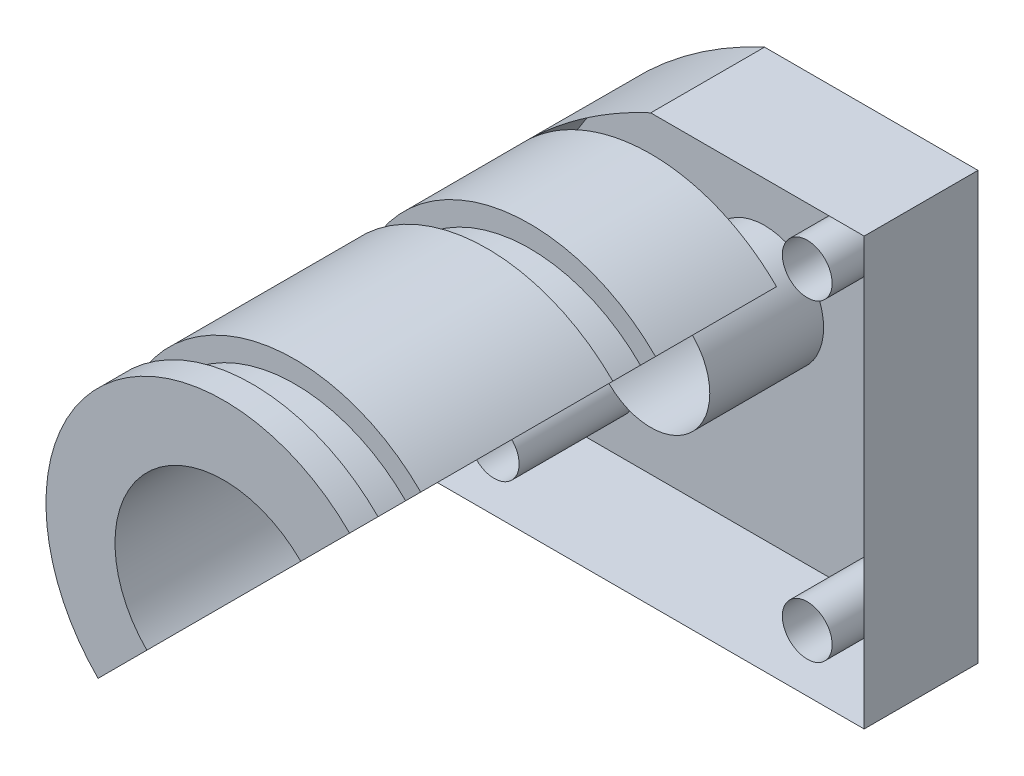
SolidWorks part; units mm, degrees
ref_plane "Ön Düzlem" through (0, 0, 0) normal (0, 0, 1) x (1, 0, 0)
ref_plane "Üst Düzlem" through (0, 0, 0) normal (0, 1, 0) x (1, 0, 0)
ref_plane "Sağ Düzlem" through (0, 0, 0) normal (1, 0, 0) x (0, 0, -1)
sketch "Çizim1" plane through (0, 0, 0) normal (0, 0, 1) x (1, 0, 0)
  line L1 (0, 0) -> (30, 0)
  line L2 (0, 0) -> (0, 30)
  line L3 (0, 30) -> (30, 30)
  line L4 (30, 0) -> (30, 30)
  dimension "D1" = 30
extrude "Yükseklik-Ekstrüzyon1" add sketch "Çizim1" along normal blind 8
sketch "Çizim2" plane through (0, 0, 8) normal (0, 0, 1) x (1, 0, 0)
  line L0 (6.1612, 6.1612) -> (9.5906, 9.5906)
  line L1 (20.4094, 20.4094) -> (23.8388, 23.8388)
  line L3 (30, 30) -> (0, 0) construction
  arc A0 (6.1612, 6.1612) -> (23.8388, 23.8388) centre (15, 15) cw
  arc A1 (9.5906, 9.5906) -> (20.4094, 20.4094) centre (15, 15) cw
  dimension "D1" = 12.5
  dimension "D2" = 7.65
sketch "Çizim3" plane through (0, 0, 8) normal (0, 0, 1) x (1, 0, 0)
  line L0 (30, 30) -> (0, 30) construction
  line L1 (0, 30) -> (0, 0) construction
  line L2 (30, 0) -> (30, 30) construction
  line L3 (0, 0) -> (30, 0) construction
  circle A0 centre (4, 26) radius 1.75
  circle A1 centre (4, 4) radius 1.75
  circle A2 centre (26, 26) radius 1.75
  circle A3 centre (26, 4) radius 1.75
  point P8 (0, 0)
  point P9 (0, 0)
  point P10 (0, 0)
  point P11 (0, 0)
  dimension "D1" = 3.5
  dimension "D2" = 4
  dimension "D3" = 4
  dimension "D4" = 4
  dimension "D5" = 4
extrude "Kes-Ekstrüzyon1" cut sketch "Çizim3" against normal blind 30
extrude "Yükseklik-Ekstrüzyon3" add sketch "Çizim2" along normal blind 30
sketch "Çizim4" plane through (0, 0, 8) normal (0, 0, 1) x (1, 0, 0)
  line L0 (0, 30) -> (0, 0) construction
  line L1 (30, 30) -> (0, 30) construction
  line L2 (0, 15) -> (0, 30)
  line L3 (0, 30) -> (15, 30)
  arc A0 (0, 15) -> (15, 30) centre (27.8377, 2.1623) cw
  arc A1 (23.8388, 23.8388) -> (6.1612, 6.1612) centre (15, 15) ccw construction
extrude "Kes-Ekstrüzyon2" cut sketch "Çizim4" against normal blind 30
sketch "Çizim5" plane through (0, 0, 8) normal (0, 0, 1) x (1, 0, 0)
  circle A0 centre (15, 15) radius 4.15
  arc A1 (20.4094, 20.4094) -> (9.5906, 9.5906) centre (15, 15) ccw construction
  dimension "D1" = 8.3
extrude "Kes-Ekstrüzyon3" cut sketch "Çizim5" against normal blind 30
sketch "Çizim6" plane through (0, 0, 0) normal (0.7071, -0.7071, 0) x (0, 0, -1)
  line L0 (-38, 33.7132) -> (-8, 33.7132) construction
  line L1 (-36, 33.7132) -> (-33, 33.7132)
  line L2 (-36, 33.7132) -> (-36, 32.2132)
  line L3 (-36, 32.2132) -> (-33, 32.2132)
  line L4 (-33, 33.7132) -> (-33, 32.2132)
  line L5 (-38, 28.8632) -> (-38, 33.7132) construction
  line L6 (-16.5, 33.7132) -> (-19.5, 33.7132)
  line L7 (-16.5, 33.7132) -> (-16.5, 32.2132)
  line L8 (-16.5, 32.2132) -> (-19.5, 32.2132)
  line L9 (-19.5, 33.7132) -> (-19.5, 32.2132)
  line L10 (-42.3212, 21.2132) -> (6.3859, 21.2132) construction
  line L11 (-38, 28.8632) -> (-38, 13.5632) construction
  dimension "D1" = 3
  dimension "D2" = 3
  dimension "D3" = 13.5
  dimension "D4" = 2
  dimension "D5" = 1.5
  dimension "D6" = 12.5
revolve "Kes-Döndür1" cut sketch "Çizim6" angle 360 about L10
